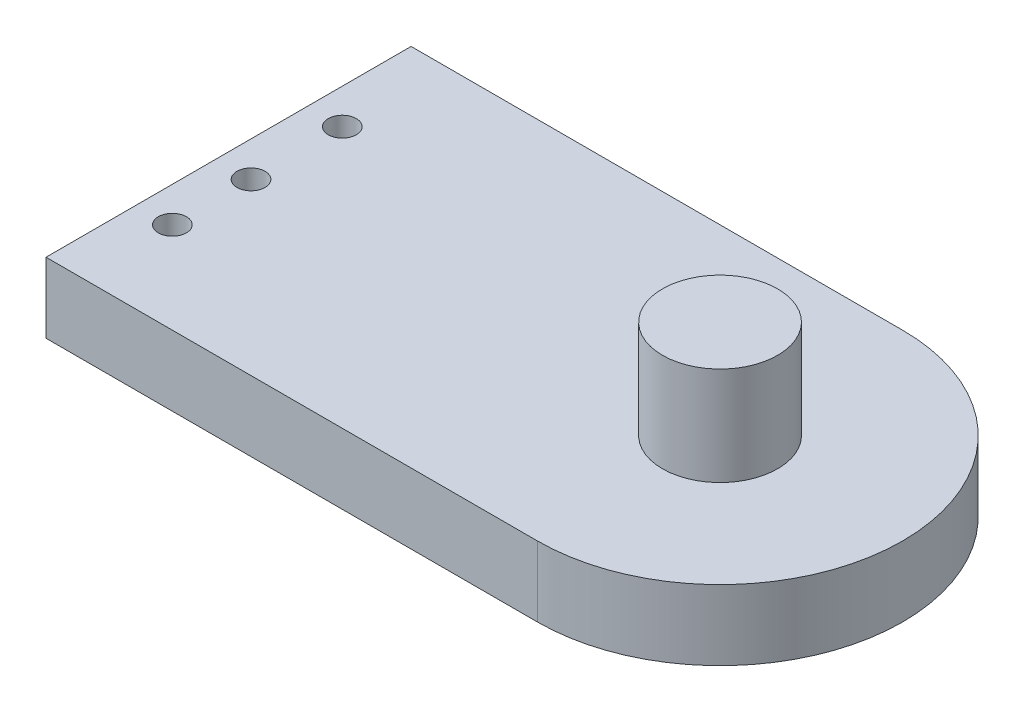
SolidWorks part; units mm, degrees
ref_plane "Front Plane" through (0, 0, 0) normal (0, 0, 1) x (1, 0, 0)
ref_plane "Top Plane" through (0, 0, 0) normal (0, 1, 0) x (1, 0, 0)
ref_plane "Right Plane" through (0, 0, 0) normal (1, 0, 0) x (0, 0, -1)
sketch "Sketch1" plane through (0, 0, 0) normal (0, 1, 0) x (1, 0, 0)
  line L1 (0, 0) -> (35, 0)
  line L2 (0, 0) -> (0, 26)
  line L3 (0, 26) -> (35, 26)
  line L4 (35, 0) -> (35, 26)
  circle A0 centre (35, 13) radius 13
  dimension "D3" = 26
  dimension "D1" = 26
  dimension "D2" = 35
extrude "Boss-Extrude1" add sketch "Sketch1" along normal blind 5 contours A0 L3 L2 L1 | L4 A0 | L4 A0
sketch "Sketch2" plane through (0, 5, 0) normal (0, 1, 0) x (1, 0, 0)
  line L0 (0, 0) -> (0, 26) construction
  circle A0 centre (35, 13) radius 4.1
  dimension "D1" = 8.2
  dimension "D2" = 35
  dimension "D3" = 13
extrude "Boss-Extrude2" add sketch "Sketch2" along normal blind 7 contours A0
sketch "Sketch3" plane through (0, 0, 0) normal (0, -1, 0) x (1, 0, 0)
  line L0 (0, 0) -> (35, 0) construction
  line L1 (0, 0) -> (0, -26) construction
  circle A0 centre (2.5, -6.5) radius 1
  circle A1 centre (2.5, -12.1) radius 1
  circle A2 centre (2.5, -18.6) radius 1
  point P0 (2.5, -6.5)
  point P2 (2.5, -12.1)
  point P4 (2.5, -18.6)
  dimension "D6" = 2
  dimension "D1" = 6.5
  dimension "D2" = 5.6
  dimension "D3" = 6.5
  dimension "D4" = 2.5
  dimension "D5" = 2.5
hole_wizard "Ø2.0mm Dowel Hole2" positions "Sketch3" profile "Sketch4" hole size "Ø2.0" standard "ANSI Metric"
sketch "Sketch4" plane through (2.5, 0, -6.5) normal (1, 0, 0) x (0, 0, -1)
  line L0 (0, 0) -> (0, 7.6009)
  line L1 (0, 7.6009) -> (1, 7)
  line L2 (1, 7) -> (1, 0)
  line L5 (1, 0) -> (0, 0)
  line L10 (0, 7.6009) -> (-1, 7) construction
  line L11 (0, -6.35) -> (0, 107.95) construction
  dimension "Hole Dia." = 2
  dimension "Hole Depth" = 7
  dimension "Drill Angle" = 118
